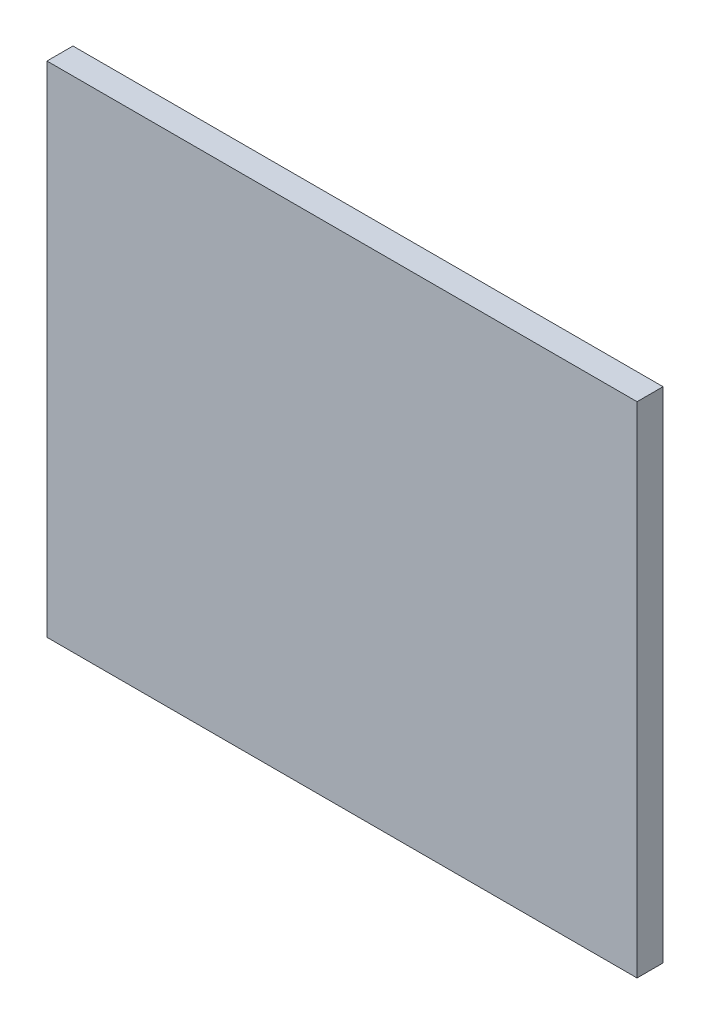
SolidWorks part; units mm, degrees
ref_plane "Plano frontal" through (0, 0, 0) normal (0, 0, 1) x (1, 0, 0)
ref_plane "Plano superior" through (0, 0, 0) normal (0, 1, 0) x (1, 0, 0)
ref_plane "Plano direito" through (0, 0, 0) normal (1, 0, 0) x (0, 0, -1)
sketch "Esboço5" plane through (0, 0, 0) normal (0, 0, 1) x (1, 0, 0)
  line L1 (140.0983, -31.927) -> (-86.9017, -31.927)
  line L2 (140.0983, -31.927) -> (140.0983, 160.073)
  line L3 (140.0983, 160.073) -> (-86.9017, 160.073)
  line L4 (-86.9017, -31.927) -> (-86.9017, 160.073)
  line L5 (140.0983, -31.927) -> (-86.9017, 160.073) construction
  line L6 (140.0983, 160.073) -> (-86.9017, -31.927) construction
  point P0 (26.5983, 64.073)
  dimension "D1" = 192
  dimension "D2" = 227
extrude "Extrusão1" add sketch "Esboço5" against normal blind 10
sketch "Esboço7" plane through (0, 0, 0) normal (0, 0, 1) x (1, 0, 0)
  line L0 (140.0983, 160.073) -> (-86.9017, 160.073) construction
  line L1 (140.0983, 160.073) -> (125.0983, 160.073)
  line L2 (140.0983, 160.073) -> (140.0983, 110.073)
  line L3 (140.0983, 110.073) -> (125.0983, 110.073)
  line L4 (125.0983, 160.073) -> (125.0983, 110.073)
  line L5 (140.0983, -31.927) -> (140.0983, 160.073) construction
  line L6 (-86.9017, 160.073) -> (-86.9017, -31.927) construction
  line L7 (-86.9017, 160.073) -> (-71.9017, 160.073)
  line L8 (-86.9017, 160.073) -> (-86.9017, 110.073)
  line L9 (-86.9017, 110.073) -> (-71.9017, 110.073)
  line L10 (-71.9017, 160.073) -> (-71.9017, 110.073)
  line L11 (125.0983, 110.073) -> (66.5983, 110.073)
  line L12 (-71.9017, 110.073) -> (-13.4017, 110.073)
  line L13 (66.5983, 110.073) -> (66.5983, 38.073)
  line L14 (-13.4017, 110.073) -> (-13.4017, 38.073)
  circle A0 centre (-71.9017, 110.073) radius 2
  circle A1 centre (125.0983, 110.073) radius 2
  circle A2 centre (-13.4017, 110.073) radius 2
  circle A3 centre (66.5983, 110.073) radius 2
  dimension "D5" = 4
  dimension "D6" = 4
  dimension "D9" = 4
  dimension "D10" = 4
  dimension "D1" = 50
  dimension "D2" = 15
  dimension "D3" = 50
  dimension "D4" = 15
  dimension "D7" = 58.5
  dimension "D8" = 58.5
  dimension "D11" = 72
  dimension "D12" = 72
sketch "Esboço9" plane through (0, 0, 0) normal (0, 0, 1) x (1, 0, 0)
  line L0 (66.5983, 38.073) -> (46.5983, 38.073)
  line L1 (46.5983, -31.927) -> (46.5983, -16.927)
  line L2 (-86.9017, -31.927) -> (140.0983, -31.927) construction
  line L3 (46.5983, -16.927) -> (46.5983, 67.473)
  line L4 (46.5983, 67.473) -> (6.5983, 67.473)
  line L5 (46.5983, -16.927) -> (6.5983, -16.927)
  line L6 (125.0983, 110.073) -> (125.0983, 38.073)
  line L7 (-71.9017, 110.073) -> (-71.9017, 38.073)
  circle A0 centre (66.5983, 38.073) radius 2
  circle A1 centre (-13.4017, 38.073) radius 2
  circle A2 centre (46.5983, -16.927) radius 2
  circle A3 centre (46.5983, 67.473) radius 2
  circle A4 centre (6.5983, 67.473) radius 2
  circle A5 centre (6.5983, -16.927) radius 2
  circle A6 centre (125.0983, 38.073) radius 2
  circle A7 centre (-71.9017, 38.073) radius 2
  dimension "D1" = 4
  dimension "D2" = 4
  dimension "D5" = 4
  dimension "D7" = 4
  dimension "D9" = 4
  dimension "D11" = 4
  dimension "D12" = 4
  dimension "D13" = 4
  dimension "D3" = 20
  dimension "D4" = 15
  dimension "D6" = 84.4
  dimension "D8" = 40
  dimension "D10" = 40
